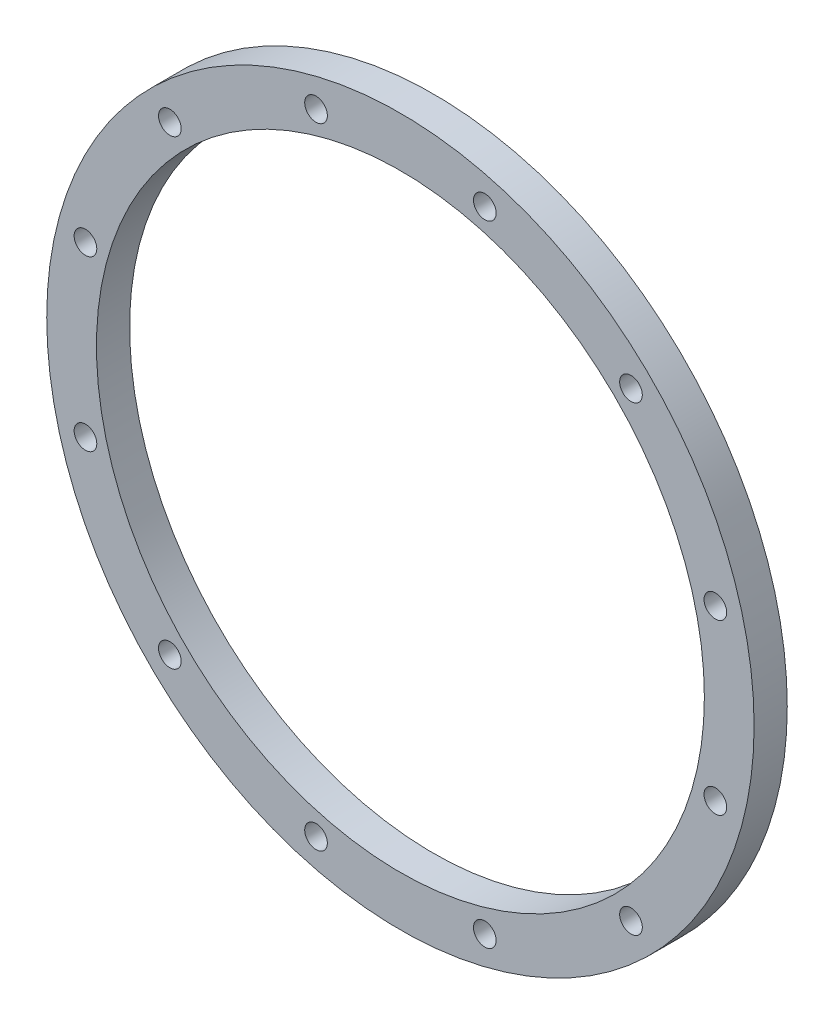
SolidWorks part; units mm, degrees
ref_plane "Front Plane" through (0, 0, 0) normal (0, 0, 1) x (1, 0, 0)
ref_plane "Top Plane" through (0, 0, 0) normal (0, 1, 0) x (1, 0, 0)
ref_plane "Right Plane" through (0, 0, 0) normal (1, 0, 0) x (0, 0, -1)
sketch "Sketch1" plane through (0, 0, 0) normal (0, 0, 1) x (1, 0, 0)
  circle A0 centre (-89.0728, 47.2587) radius 64
  circle A1 centre (-89.0728, 47.2587) radius 55
  circle A2 centre (-32.0832, 62.529) radius 2.05
  circle A3 centre (-32.0832, 31.9884) radius 2.05
  circle A4 centre (-47.3535, 5.5394) radius 2.05
  circle A5 centre (-73.8025, -9.7309) radius 2.05
  circle A6 centre (-104.3431, -9.7309) radius 2.05
  circle A7 centre (-130.7921, 5.5394) radius 2.05
  circle A8 centre (-146.0624, 31.9884) radius 2.05
  circle A9 centre (-146.0624, 62.529) radius 2.05
  circle A10 centre (-130.7921, 88.978) radius 2.05
  circle A11 centre (-104.3431, 104.2483) radius 2.05
  circle A12 centre (-73.8025, 104.2483) radius 2.05
  circle A13 centre (-47.3535, 88.978) radius 2.05
  point P29 (-89.0728, 47.2587)
  dimension "D1" = 128
  dimension "D2" = 110
  dimension "D3" = 4.1
  dimension "D4" = 12
extrude "Boss-Extrude1" add sketch "Sketch1" along normal blind 6
